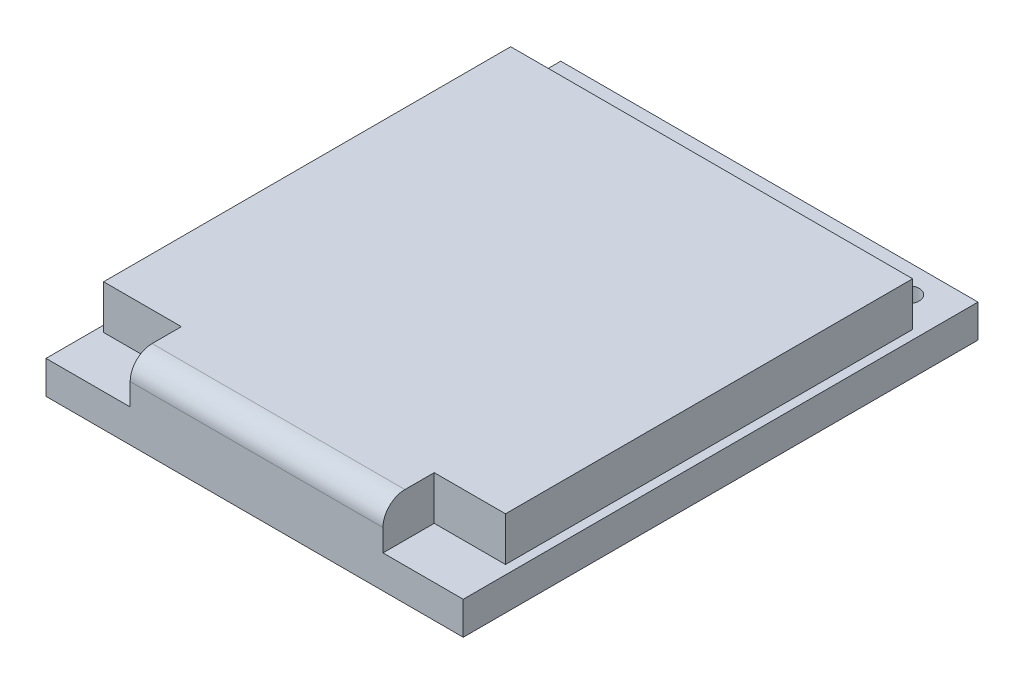
SolidWorks part; units mm, degrees
ref_plane "Front Plane" through (0, 0, 0) normal (0, 0, 1) x (1, 0, 0)
ref_plane "Top Plane" through (0, 0, 0) normal (0, 1, 0) x (1, 0, 0)
ref_plane "Right Plane" through (0, 0, 0) normal (1, 0, 0) x (0, 0, -1)
sketch "Sketch1" plane through (0, 0, 0) normal (0, 1, 0) x (1, 0, 0)
  line L0 (1.88, -1.3) -> (4.42, -1.3) construction
  line L1 (0, 0) -> (19, 0)
  line L2 (0, 0) -> (0, -23.44)
  line L3 (0, -23.44) -> (19, -23.44)
  line L4 (19, 0) -> (19, -23.44)
  circle A0 centre (1.88, -1.3) radius 0.5
  circle A1 centre (4.42, -1.3) radius 0.5
  circle A2 centre (6.96, -1.3) radius 0.5
  circle A3 centre (9.5, -1.3) radius 0.5
  circle A4 centre (12.04, -1.3) radius 0.5
  circle A5 centre (14.58, -1.3) radius 0.5
  circle A6 centre (17.12, -1.3) radius 0.5
  dimension "D3" = 7
  dimension "D5" = 1
  dimension "D1" = 19
  dimension "D2" = 23.44
  dimension "D4" = 2.54
  dimension "D6" = 1.88
  dimension "D7" = 1.3
extrude "Boss-Extrude1" add sketch "Sketch1" along normal blind 1.5
sketch "Sketch3" plane through (0, 1.5, 0) normal (0, 1, 0) x (1, 0, 0)
  line L0 (3.8324, -21.107) -> (3.8324, -23.44)
  line L1 (0.2901, -2.5692) -> (18.5918, -2.5692)
  line L2 (0.2901, -2.5692) -> (0.2901, -21.107)
  line L3 (0.2901, -21.107) -> (3.8324, -21.107)
  line L4 (18.5918, -2.5692) -> (18.5918, -21.107)
  line L5 (0, -23.44) -> (19, -23.44) construction
  line L6 (15.3447, -21.107) -> (15.3447, -23.44)
  line L7 (15.3447, -21.107) -> (18.5918, -21.107)
  line L8 (3.8324, -23.44) -> (15.3447, -23.44)
extrude "Boss-Extrude2" add sketch "Sketch3" along normal blind 2
fillet "Fillet1" radius 1 1 edges at (9.5886, 3.5, 23.44)
